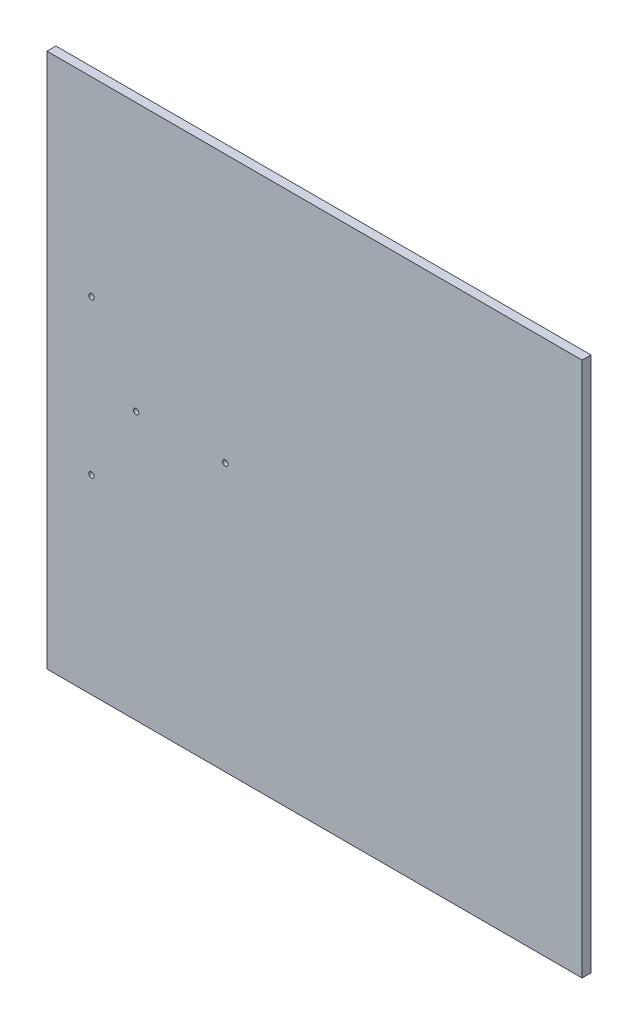
SolidWorks part; units mm, degrees
ref_plane "Front Plane" through (0, 0, 0) normal (0, 0, 1) x (1, 0, 0)
ref_plane "Top Plane" through (0, 0, 0) normal (0, 1, 0) x (1, 0, 0)
ref_plane "Right Plane" through (0, 0, 0) normal (1, 0, 0) x (0, 0, -1)
sketch "Sketch1" plane through (0, 0, 0) normal (0, 0, 1) x (1, 0, 0)
  line L1 (-149.1124, 66.568) -> (150.8876, 66.568)
  line L2 (-149.1124, 66.568) -> (-149.1124, -233.432)
  line L3 (-149.1124, -233.432) -> (150.8876, -233.432)
  line L4 (150.8876, 66.568) -> (150.8876, -233.432)
  dimension "D1" = 300
  dimension "D2" = 300
extrude "Boss-Extrude1" add sketch "Sketch1" along normal blind 5
sketch "Sketch5" plane through (0, 0, 5) normal (0, 0, 1) x (1, 0, 0)
  line L0 (-149.1124, 66.568) -> (-149.1124, -233.432) construction
  circle A0 centre (-99.1124, -83.432) radius 1.5
  dimension "D1" = 50
extrude "Cut-Extrude3" cut sketch "Sketch5" against normal through all
sketch "Sketch6" plane through (0, 0, 5) normal (0, 0, 1) x (1, 0, 0)
  line L0 (-99.1124, -83.432) -> (-50.6124, -83.432) construction
  line L1 (-99.1124, -83.432) -> (-124.1124, -40.1307) construction
  circle A1 centre (-49.1124, -83.432) radius 1.5
  circle A2 centre (-124.1124, -40.1307) radius 1.5
  circle A3 centre (-124.1124, -126.7332) radius 1.5
  dimension "D3" = 3
  dimension "D4" = 3
  dimension "D2" = 120
extrude "Cut-Extrude5" cut sketch "Sketch6" against normal through all
